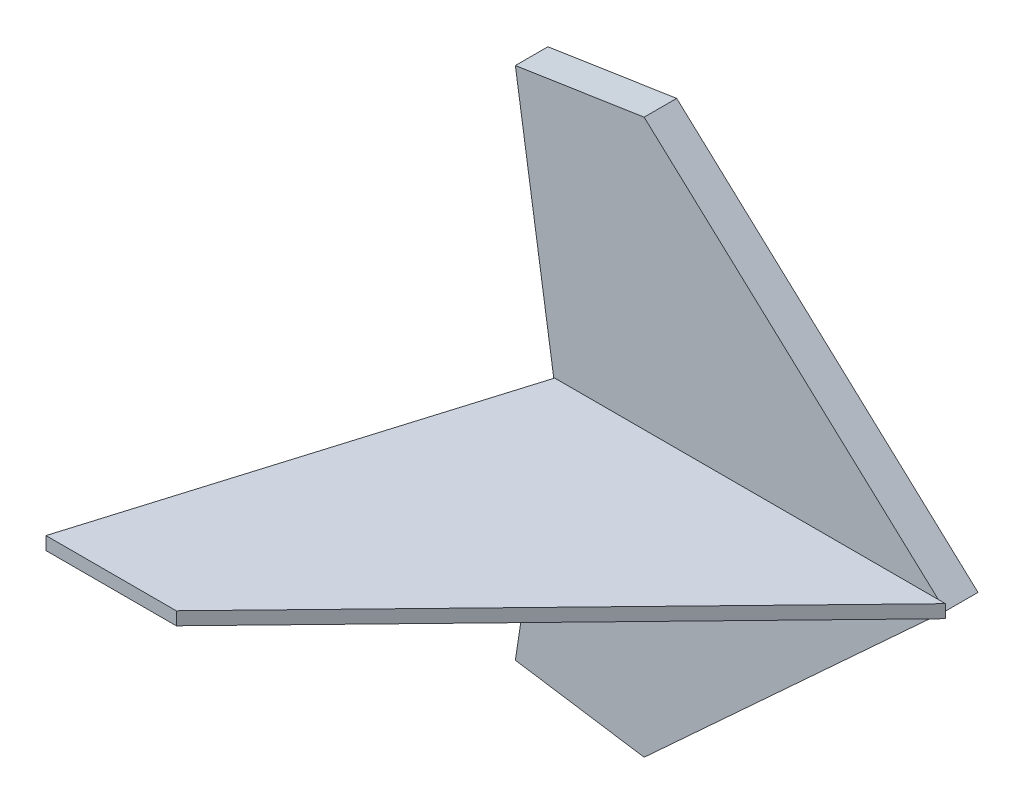
SolidWorks part; units mm, degrees
ref_plane "Front Plane" through (0, 0, 0) normal (0, 0, 1) x (1, 0, 0)
ref_plane "Top Plane" through (0, 0, 0) normal (0, 1, 0) x (1, 0, 0)
ref_plane "Right Plane" through (0, 0, 0) normal (1, 0, 0) x (0, 0, -1)
sketch "Sketch3" plane through (0, 0, 0) normal (0, 0, 1) x (1, 0, 0)
  line L0 (0, 0) -> (30, 0)
  line L1 (0, 0) -> (-3.0181, 19.771)
  line L2 (-3.0181, 19.771) -> (6.8674, 21.28)
  line L3 (6.8674, 21.28) -> (30, 0)
  line L4 (0, 0) -> (70.8656, 0) construction
  line L5 (-3.0181, -19.771) -> (6.8674, -21.28)
  line L6 (0, 0) -> (-3.0181, -19.771)
  line L7 (6.8674, -21.28) -> (30, 0)
  dimension "D1" = 30
  dimension "D2" = 20
  dimension "D3" = 10
extrude "Boss-Extrude1" add sketch "Sketch3" along normal blind 2.5 contours L3 L2 L1 L0 | L5 L7 L0 L6
sketch "Sketch4" plane through (0, 0, 0) normal (0, 1, 0) x (1, 0, 0)
  line L0 (-9.0542, -32.5) -> (0, -2.5)
  line L1 (-9.0542, -32.5) -> (0.9458, -32.5)
  line L2 (0.9458, -32.5) -> (30, -2.5)
  line L3 (0, -2.5) -> (30, -2.5)
  dimension "D1" = 30
  dimension "D2" = 10
extrude "Boss-Extrude2" add sketch "Sketch4" along normal mid plane 1 separate body
sketch "Sketch5" plane through (0, 0, 0) normal (0, 0, -1) x (-1, 0, 0)
  line L1 (-11.9981, 0.902) -> (-9.9981, 0.902)
  line L2 (-11.9981, 0.902) -> (-11.9981, -1.098)
  line L3 (-11.9981, -1.098) -> (-9.9981, -1.098)
  line L4 (-9.9981, 0.902) -> (-9.9981, -1.098)
  line L5 (-11.9981, 0.902) -> (-9.9981, -1.098) construction
  line L6 (-11.9981, -1.098) -> (-9.9981, 0.902) construction
  point P0 (-10.9981, -0.098)
  dimension "D1" = 2
  dimension "D2" = 2
extrude "Boss-Extrude3" add sketch "Sketch5" along normal blind 7.5
